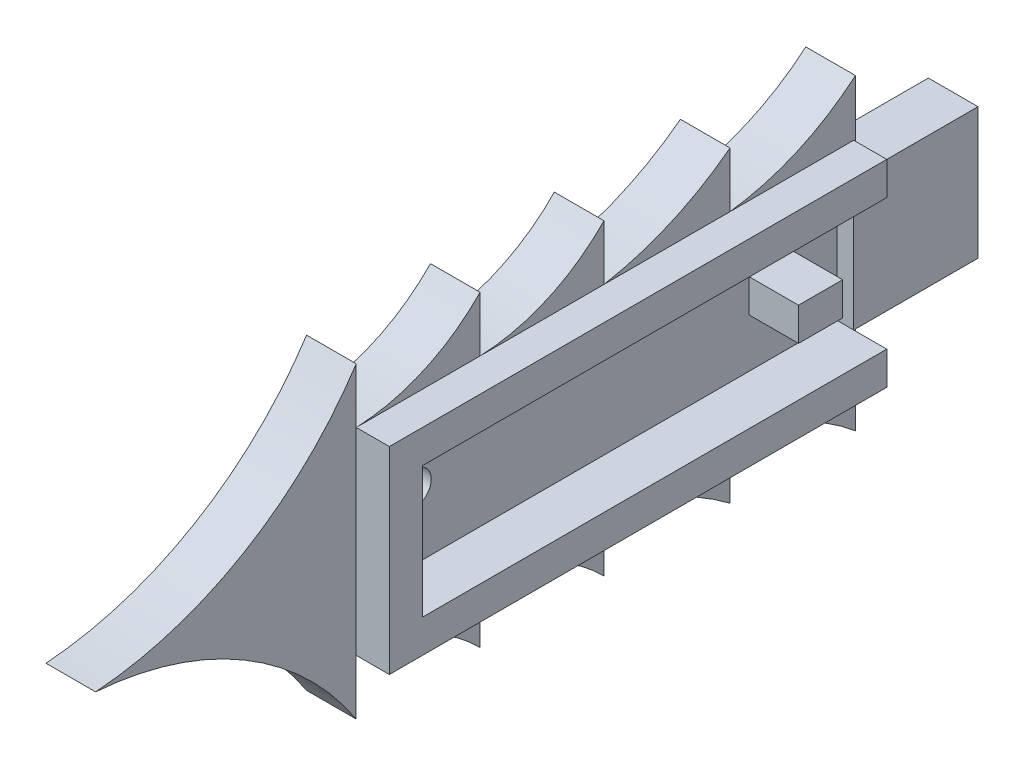
SolidWorks part; units mm, degrees
ref_plane "Front Plane" through (0, 0, 0) normal (1, 0, 0) x (0, 1, 0)
ref_plane "Top Plane" through (0, 0, 0) normal (0, 0, 1) x (0, 1, 0)
ref_plane "Right Plane" through (0, 0, 0) normal (0, 1, 0) x (-1, 0, 0)
sketch "Sketch1" plane through (0, 0, 0) normal (1, 0, 0) x (0, 1, 0)
  line L0 (-5.95, 3.8) -> (5.95, 3.8) construction
  line L1 (0, 0) -> (0, 3.8) construction
  line L2 (-1.5, -30.3) -> (1.5, -30.3) construction
  line L3 (0, -30.3) -> (0, -1.5) construction
  line L4 (-5.95, 3.8) -> (-5.95, -38.3) construction
  line L5 (5.95, 3.8) -> (5.95, -38.3) construction
  line L6 (5.95, -38.3) -> (1.5, -38.3) construction
  line L7 (1.5, -38.3) -> (1.5, -30.3) construction
  line L8 (-1.5, -30.3) -> (-1.5, -38.3) construction
  line L9 (-1.5, -38.3) -> (-5.95, -38.3) construction
  line L11 (-1.5, -30.3) -> (1.5, -30.3)
  line L12 (-1.5, -30.3) -> (-1.5, -34.3)
  line L13 (-1.5, -34.3) -> (1.5, -34.3)
  line L14 (1.5, -30.3) -> (1.5, -34.3)
  line L15 (5.95, -38.3) -> (8.95, -38.3)
  line L16 (5.95, -38.3) -> (5.95, 3.8)
  line L17 (5.95, 3.8) -> (8.95, 3.8)
  line L18 (8.95, -38.3) -> (8.95, 3.8)
  line L19 (8.95, 3.8) -> (-8.95, 3.8)
  line L20 (8.95, 3.8) -> (8.95, 6.8)
  line L21 (8.95, 6.8) -> (-8.95, 6.8)
  line L22 (-8.95, 3.8) -> (-8.95, 6.8)
  line L23 (-5.95, -38.3) -> (-8.95, -38.3)
  line L24 (-5.95, -38.3) -> (-5.95, 3.8)
  line L25 (-5.95, 3.8) -> (-8.95, 3.8)
  line L26 (-8.95, -38.3) -> (-8.95, 3.8)
  circle A0 centre (0, 0) radius 1.5 construction
  dimension "D1" = 3
  dimension "D2" = 3.8
  dimension "D3" = 11.9
  dimension "D4" = 34.1
  dimension "D5" = 3
  dimension "D6" = 8
  dimension "D7" = 3
  dimension "D8" = 3
  dimension "D9" = 3
extrude "Boss-Extrude1" add sketch "Sketch1" along normal blind 12 contours L22 L19 L17 L20 L21 | L26 L23 L24 L19 | L15 L18 L17 L16 | L12 L11 L14 L13
ref_plane "Plane1" through (12, 8.95, 6.8) normal (0, 0, 1) x (1, 0, 0)
sketch "Sketch3" plane through (0, 0, 0) normal (-1, 0, 0) x (0, 0, 1)
  line L0 (6.8, -3.4525) -> (6.8, 21.3525) construction
  line L1 (-38.3, -8.95) -> (6.8, -8.95)
  line L2 (-38.3, -8.95) -> (-38.3, 8.95)
  line L3 (-38.3, 8.95) -> (6.8, 8.95)
  line L4 (6.8, -8.95) -> (6.8, 8.95)
  line L5 (-38.3, 8.95) -> (6.8, 8.95) construction
  circle A0 centre (0, 0) radius 1.5
extrude "Boss-Extrude2" add sketch "Sketch3" along normal blind 3
sketch "Sketch5" plane through (-3, 0, 0) normal (-1, 0, 0) x (0, -1, 0)
  line L0 (-8.95, -38.3) -> (-8.95, 3.8) construction
  line L1 (-13.95, -49.5728) -> (13.95, -49.5728)
  line L2 (-13.95, -49.5728) -> (-13.95, 21.5835)
  line L4 (13.95, -49.5728) -> (13.95, 20.9272)
  line L5 (8.95, -38.3) -> (8.95, 3.8) construction
  line L8 (-13.95, 21.5835) -> (-13.95, 30.4272)
  line L9 (-13.95, 30.4272) -> (13.95, 30.4272)
  line L10 (13.95, 20.9272) -> (13.95, 30.4272)
  dimension "D1" = 5
  dimension "D2" = 5
  dimension "D3" = 9.5
  dimension "D4" = 80
extrude "Boss-Extrude4" add sketch "Sketch5" against normal blind 4.5
sketch "Sketch6" plane through (-3, 0, 0) normal (-1, 0, 0) x (0, -1, 0)
  line L0 (0, 30.4272) -> (0, -49.5728) construction
  line L1 (-13.95, 30.4272) -> (13.95, 30.4272) construction
  line L2 (-13.95, -49.5728) -> (13.95, -49.5728) construction
  line L3 (-13.95, -49.5728) -> (-13.95, 30.4272) construction
  line L4 (3.4525, 6.8) -> (-21.3525, 6.8) construction
  line L5 (-13.95, -49.5728) -> (-13.95, 30.4272) construction
  line L6 (-8.95, -38.3) -> (-8.95, 6.8) construction
  line L7 (-8.95, 6.8) -> (-8.95, -38.3) construction
  line L8 (-8.95, -4.4306) -> (-13.95, -4.4306)
  line L9 (-13.95, -15.6611) -> (-8.95, -15.6611)
  line L10 (-13.95, -27.0926) -> (-8.95, -27.0926)
  line L11 (-13.95, -38.4631) -> (-5.95, -38.4631)
  line L12 (-5.95, -38.4631) -> (-5.95, -49.5728)
  line L13 (-5.95, -38.3) -> (-5.95, -49.5728) construction
  line L14 (-13.95, -49.5728) -> (13.95, -49.5728) construction
  line L15 (-8.95, 6.8) -> (-13.95, 6.8)
  line L16 (0, 30.4272) -> (0, 38.2073)
  line L17 (0, 38.2073) -> (-27.4952, 38.2073)
  line L18 (-27.4952, 38.2073) -> (-27.4952, -49.5728)
  line L19 (-27.4952, -49.5728) -> (-5.95, -49.5728)
  arc A2 (-13.95, 6.8) -> (0, 30.4272) centre (-30.8955, 32.7368) ccw
  arc A3 (-13.95, -4.4306) -> (-8.95, 6.8) centre (-25.4501, 7.4177) ccw
  arc A4 (-13.95, -15.6611) -> (-8.95, -4.4306) centre (-25.4501, -3.8128) ccw
  arc A5 (-8.95, -15.6611) -> (-13.95, -27.0926) centre (-34.922, -11.1105) cw
  arc A6 (-8.95, -27.0926) -> (-13.95, -38.4631) centre (-30.5316, -24.387) cw
extrude "Cut-Extrude4" cut sketch "Sketch6" against normal through all both and the other way through all
mirror "Mirror1" about plane through (0, 0, 0) normal (0, 1, 0) of "Cut-Extrude4"
sketch "Sketch7" plane through (12, 0, 0) normal (1, 0, 0) x (0, 1, 0)
  line L1 (-8.95, 6.8) -> (8.95, 6.8)
  line L2 (-8.95, 6.8) -> (-8.95, -38.3)
  line L3 (-8.95, -38.3) -> (8.95, -38.3)
  line L4 (8.95, 6.8) -> (8.95, -38.3)
extrude "Cut-Extrude5" cut sketch "Sketch7" against normal offset from surface 3 and the other way through all up to face at (1.5, 0, 10.8741)
